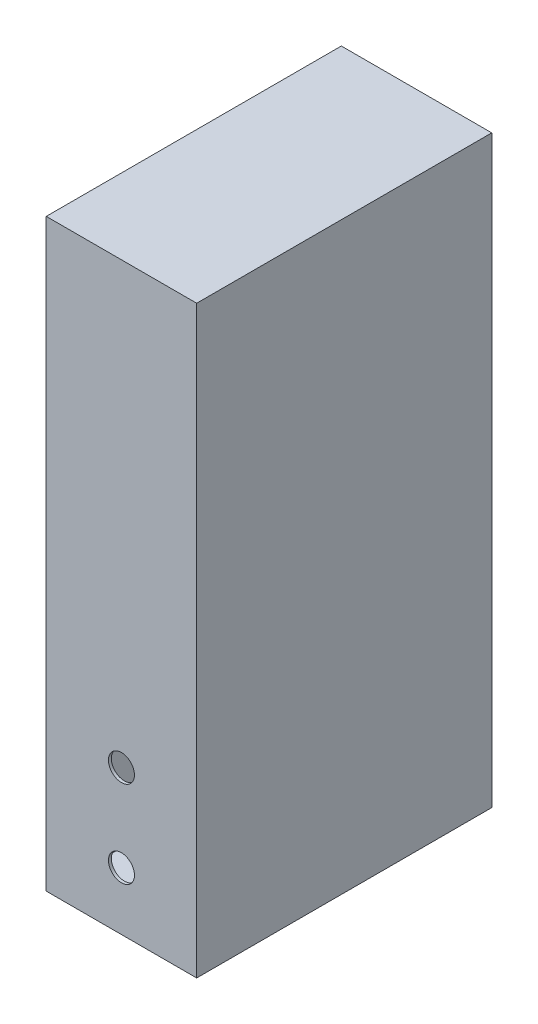
SolidWorks part; units mm, degrees
ref_plane "Plan de face" through (0, 0, 0) normal (0, 0, 1) x (1, 0, 0)
ref_plane "Plan de dessus" through (0, 0, 0) normal (0, 1, 0) x (1, 0, 0)
ref_plane "Plan de droite" through (0, 0, 0) normal (1, 0, 0) x (0, 0, -1)
sketch "Esquisse1" plane through (0, 0, 0) normal (0, 0, 1) x (1, 0, 0)
  line L1 (-26, -101) -> (26, -101)
  line L2 (-26, -101) -> (-26, 101)
  line L3 (-26, 101) -> (26, 101)
  line L4 (26, -101) -> (26, 101)
  line L5 (-26, -101) -> (26, 101) construction
  line L6 (-26, 101) -> (26, -101) construction
  point P0 (0, 0)
  dimension "D1" = 202
  dimension "D2" = 52
extrude "Boss.-Extru.1" add sketch "Esquisse1" along normal blind 102
shell "Coque1" thickness 1
sketch "Esquisse2" plane through (0, 0, 102) normal (0, 0, 1) x (1, 0, 0)
  line L1 (-25, -100) -> (25, -100)
  line L2 (-25, -100) -> (-25, 100)
  line L3 (-25, 100) -> (25, 100)
  line L4 (25, -100) -> (25, 100)
  line L5 (-25, -100) -> (25, 100) construction
  line L6 (-25, 100) -> (25, -100) construction
  point P0 (0, 0)
extrude "Boss.-Extru.2" add sketch "Esquisse2" against normal blind 1
sketch "Esquisse3" plane through (0, 0, 102) normal (0, 0, 1) x (1, 0, 0)
  line L0 (-26, -101) -> (26, -101) construction
  line L1 (-26, 101) -> (-26, -101) construction
  circle A0 centre (0, -81) radius 4.5
  circle A1 centre (0, -51) radius 4.5
  dimension "D1" = 9
  dimension "D2" = 9
  dimension "D3" = 30
  dimension "D4" = 20
  dimension "D5" = 26
  dimension "D6" = 26
extrude "Enlèv. mat.-Extru.1" cut sketch "Esquisse3" against normal blind 1
